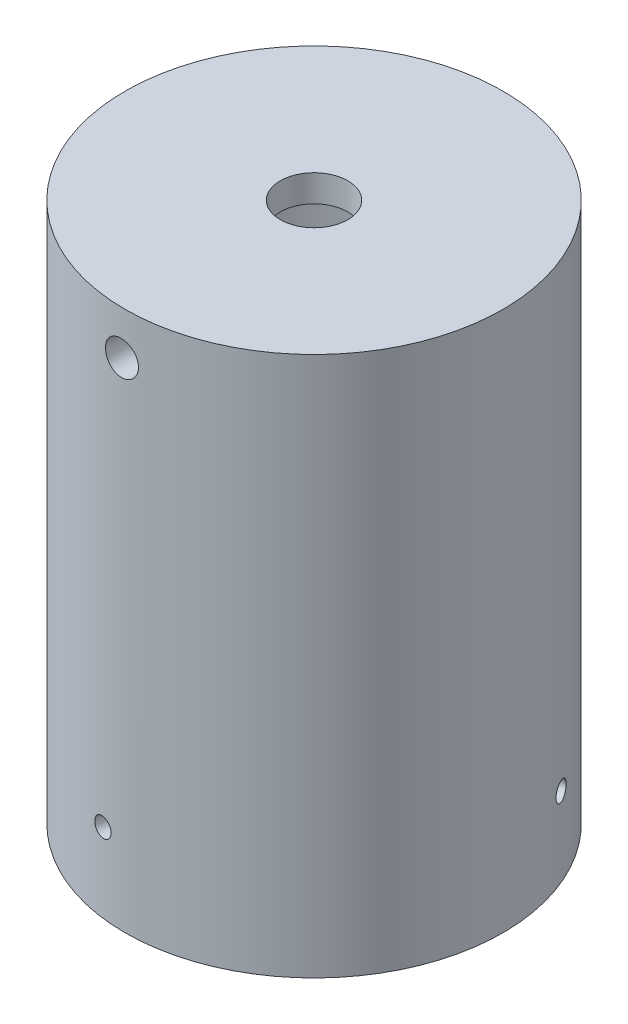
SolidWorks part; units mm, degrees
ref_plane "Front Plane" through (0, 0, 0) normal (0, 0, 1) x (1, 0, 0)
ref_plane "Top Plane" through (0, 0, 0) normal (0, 1, 0) x (1, 0, 0)
ref_plane "Right Plane" through (0, 0, 0) normal (1, 0, 0) x (0, 0, -1)
sketch "Sketch1" plane through (0, 0, 0) normal (0, 1, 0) x (1, 0, 0)
  circle A0 centre (0, 0) radius 17.78
  dimension "D1" = 35.56
extrude "Boss-Extrude1" add sketch "Sketch1" along normal blind 50.8
shell "Shell1" thickness 2.54
sketch "Sketch2" plane through (0, 48.26, 0) normal (0, -1, 0) x (1, 0, 0)
  circle A0 centre (0, 0) radius 3.175
  dimension "D1" = 6.35
extrude "Cut-Extrude1" cut sketch "Sketch2" against normal through all contours A0
hole_wizard "Tap Drill for #0-80 Tap1" positions "3DSketch2" profile "Sketch4" hole size "#0-80" standard "ANSI Inch"
sketch3d "3DSketch2"
  point P0 (-0.3631, 46.6594, 17.7763)
sketch "Sketch4" plane through (-0.3631, 46.6594, 17.7763) normal (0, 1, 0) x (0.9998, 0, 0.0204)
  line L0 (0, 0) -> (0, 7.6821)
  line L1 (0, 7.6821) -> (1.5875, 6.35)
  line L2 (1.5875, 6.35) -> (1.5875, 0)
  line L5 (1.5875, 0) -> (0, 0)
  line L10 (0, 7.6821) -> (-1.5875, 6.35) construction
  line L11 (0, -6.35) -> (0, 107.95) construction
  dimension "Hole Dia." = 3.175
  dimension "Hole Depth" = 6.35
  dimension "Drill Angle" = 100
ref_plane "Plane1" [suppressed] through (0, 7.4955, 0) normal (0, 1, 0) x (0.9873, 0, 0.1589)
hole_wizard "Tap Drill for #2-56 Tap1" positions "3DSketch4" profile "Sketch8" hole size "#2-56" standard "ANSI Inch"
sketch3d "3DSketch4"
  point P0 (-2.2477, 7.425, 17.6374)
sketch "Sketch8" plane through (-2.2477, 7.425, 17.6374) normal (0, 1, 0) x (0.992, 0, 0.1264)
  line L0 (0, 0) -> (0, 9.636)
  line L1 (0, 9.636) -> (0.889, 8.89)
  line L2 (0.889, 8.89) -> (0.889, 0)
  line L5 (0.889, 0) -> (0, 0)
  line L10 (0, 9.636) -> (-0.889, 8.89) construction
  line L11 (0, -6.35) -> (0, 107.95) construction
  dimension "Hole Dia." = 1.778
  dimension "Hole Depth" = 8.89
  dimension "Drill Angle" = 100
pattern_circular "CirPattern1" count 3 every 120 about axis through (0, 50.8, 0) along (0, -1, 0) of "Tap Drill for #2-56 Tap1"
